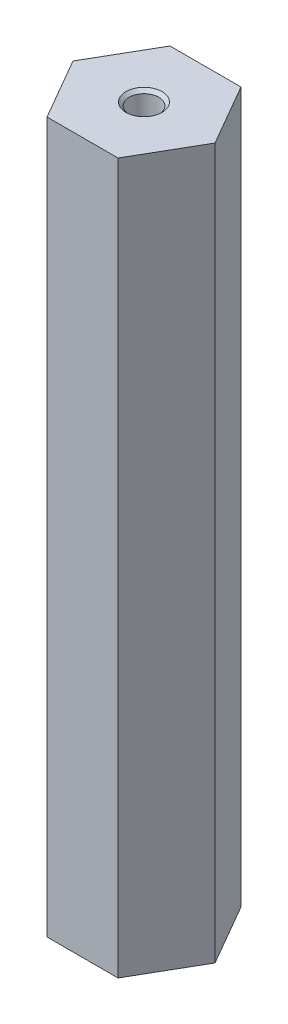
SolidWorks part; units mm, degrees
ref_plane "前视基准面" through (0, 0, 0) normal (0, 0, 1) x (1, 0, 0)
ref_plane "上视基准面" through (0, 0, 0) normal (0, 1, 0) x (1, 0, 0)
ref_plane "右视基准面" through (0, 0, 0) normal (1, 0, 0) x (0, 0, -1)
other "Configuration Table"
sketch "草图1" plane through (0, 0, 0) normal (0, 1, 0) x (1, 0, 0)
  line L1 (6, 0) -> (3, 5.1962)
  line L2 (3, 5.1962) -> (-3, 5.1962)
  line L3 (-3, 5.1962) -> (-6, 0)
  line L4 (-6, 0) -> (-3, -5.1962)
  line L5 (-3, -5.1962) -> (3, -5.1962)
  line L6 (3, -5.1962) -> (6, 0)
  circle A0 centre (0, 0) radius 5.1962 construction
  dimension "D1" = 6
extrude "凸台-拉伸1" add sketch "草图1" along normal blind 60
sketch "草图8" plane through (0, 60, 0) normal (0, 1, 0) x (1, 0, 0)
  point P0 (0, 0)
hole_wizard "M3 螺纹孔1" positions "草图8" profile "草图9" tap size "M3" standard "GB" end condition through all
sketch "草图9" plane through (0, 60, 0) normal (1, 0, 0) x (0, 0, 1)
  line L0 (0, 0) -> (0, 60)
  line L1 (0, 60) -> (1.25, 60)
  line L2 (1.25, 60) -> (1.25, 0.275)
  line L3 (1.25, 0.275) -> (1.525, 0)
  line L5 (1.525, 0) -> (0, 0)
  line L6 (-1.25, 0.275) -> (-1.525, 0) construction
  line L11 (0, -6.35) -> (0, 107.95) construction
  dimension "通孔螺纹孔钻头直径" = 2.5
  dimension "通孔螺纹孔钻头深度" = 60
  dimension "近端锥形沉头孔直径" = 3.05
  dimension "近端锥形沉头孔角度" = 90
cosmetic thread "孔螺蚊线1" parameters "D2"=3
